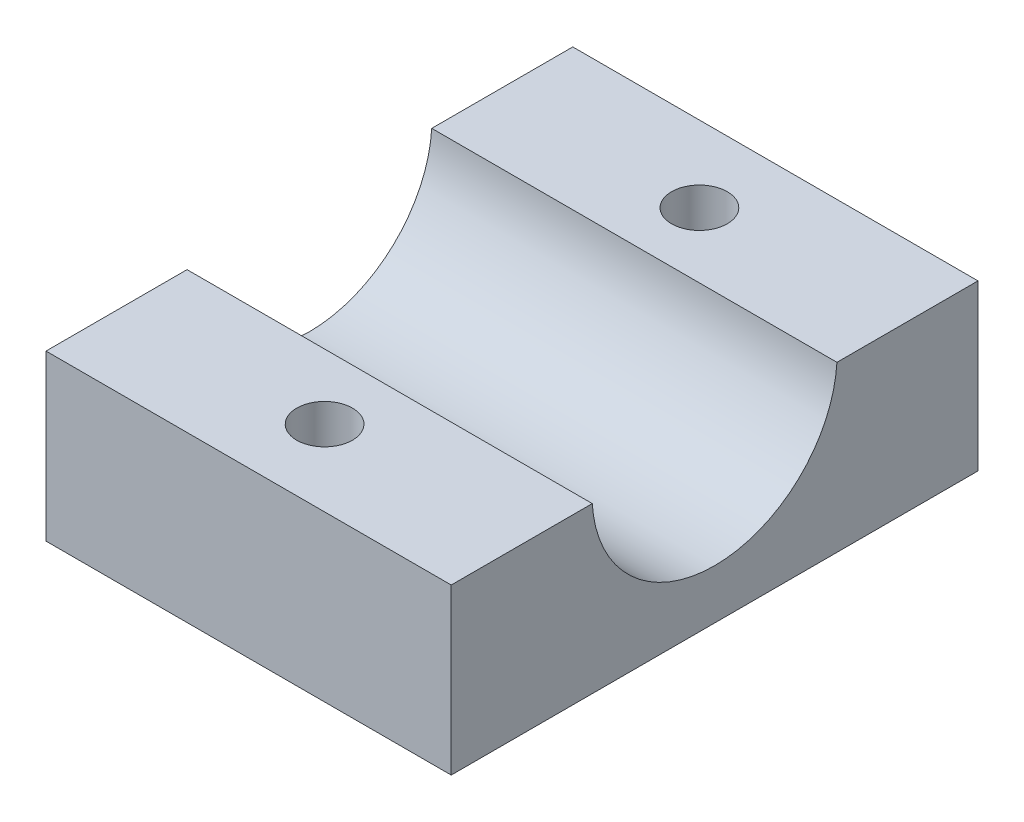
SolidWorks part; units mm, degrees
ref_plane "Front Plane" through (0, 0, 0) normal (0, 0, 1) x (1, 0, 0)
ref_plane "Top Plane" through (0, 0, 0) normal (0, 1, 0) x (1, 0, 0)
ref_plane "Right Plane" through (0, 0, 0) normal (1, 0, 0) x (0, 0, -1)
sketch "Sketch1" plane through (0, 0, 0) normal (1, 0, 0) x (0, 0, -1)
  line L0 (-26, -29) -> (26, -29)
  line L1 (26, -29) -> (26, -12.75)
  line L2 (26, -12.75) -> (-26, -12.75)
  line L3 (-26, -12.75) -> (-26, -29)
extrude "Clamp Lower Half" add sketch "Sketch1" along normal mid plane 40
sketch "Sketch2" plane through (0, 0, 0) normal (1, 0, 0) x (0, 0, -1)
  circle A0 centre (0, -12) radius 12.1
extrude "Handlebar Bore" cut sketch "Sketch2" against normal through all and the other way through all
sketch "Sketch3" plane through (0, 0, 0) normal (0, 1, 0) x (1, 0, 0)
  circle A0 centre (0, -18.5) radius 2.75
  circle A1 centre (0, 18.5) radius 2.75
extrude "M5 Clearance Holes" cut sketch "Sketch3" against normal through all and the other way through all
equation "\"BrW\" = 56.0"
equation "\"BrL\" = 80.0"
equation "\"BrH\" = 18.0"
equation "\"RailW\" = 30.0"
equation "\"RailW2\" = 38.0"
equation "\"RailH\" = 6.0"
equation "\"Slide\" = 0.3"
equation "\"StopT\" = 6.0"
equation "\"TubeD\" = 22.2"
equation "\"Liner\" = 1.0"
equation "\"ClampW\" = 40.0"
equation "\"ClampZ\" = 26.0"
equation "\"ClampY\" = -12.0"
equation "\"CapT\" = 17.0"
equation "\"Gap\" = 0.75"
equation "\"BoltZ\" = 18.5"
equation "\"InsertD\" = 6.4"
equation "\"InsertL\" = 10.0"
equation "\"BoltD\" = 5.5"
equation "\"LockZ\" = -30.0"
equation "\"LockInsD\" = 5.6"
equation "\"LockInsL\" = 8.0"
equation "\"LockClear\" = 4.5"
equation "\"DovOff\" = 0.35"
